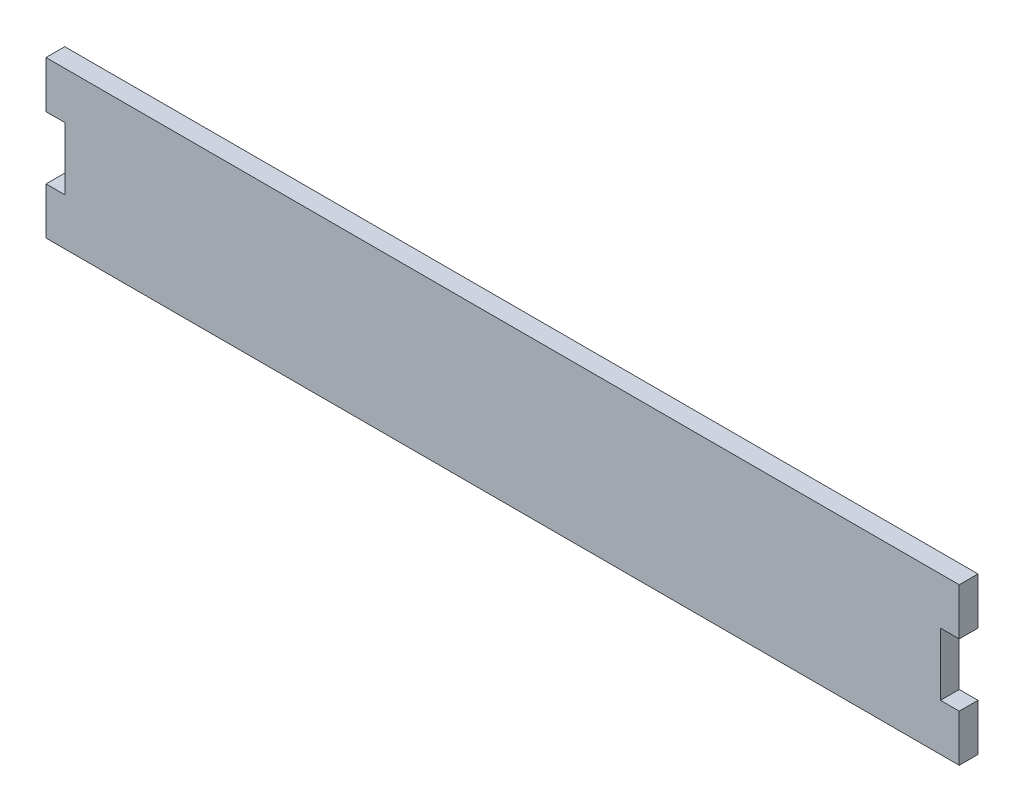
SolidWorks part; units mm, degrees
ref_plane "Plano frontal" through (0, 0, 0) normal (0, 0, 1) x (1, 0, 0)
ref_plane "Plano superior" through (0, 0, 0) normal (0, 1, 0) x (1, 0, 0)
ref_plane "Plano direito" through (0, 0, 0) normal (1, 0, 0) x (0, 0, -1)
sketch "Esboço1" plane through (0, 0, 0) normal (0, 0, 1) x (1, 0, 0)
  line L1 (0, 0) -> (292, 0)
  line L2 (0, 0) -> (0, 50)
  line L3 (0, 50) -> (292, 50)
  line L4 (292, 0) -> (292, 50)
extrude "Ressalto-extrusão1" add sketch "Esboço1" along normal blind 6
sketch "Esboço2" plane through (0, 0, 0) normal (0, 0, -1) x (-1, 0, 0)
  line L0 (-6, 0) -> (-6, 15) construction
  line L1 (0, 0) -> (-292, 0) construction
  line L2 (-6, 50) -> (-6, 35) construction
  line L3 (-292, 50) -> (0, 50) construction
  line L4 (0, 50) -> (0, 0) construction
  line L5 (-6, 15) -> (0, 15)
  line L6 (-6, 15) -> (-6, 35)
  line L7 (-6, 35) -> (0, 35)
  line L8 (0, 15) -> (0, 35)
  line L9 (-291.1245, 0) -> (-291.1245, 15) construction
  line L10 (-291.1245, 35) -> (-291.1245, 50) construction
  line L11 (-292, 0) -> (-292, 50) construction
  line L12 (-292, 15) -> (-286, 15)
  line L13 (-292, 15) -> (-292, 35)
  line L14 (-292, 35) -> (-286, 35)
  line L15 (-286, 15) -> (-286, 35)
extrude "Corte-extrusão1" cut sketch "Esboço2" against normal through all
